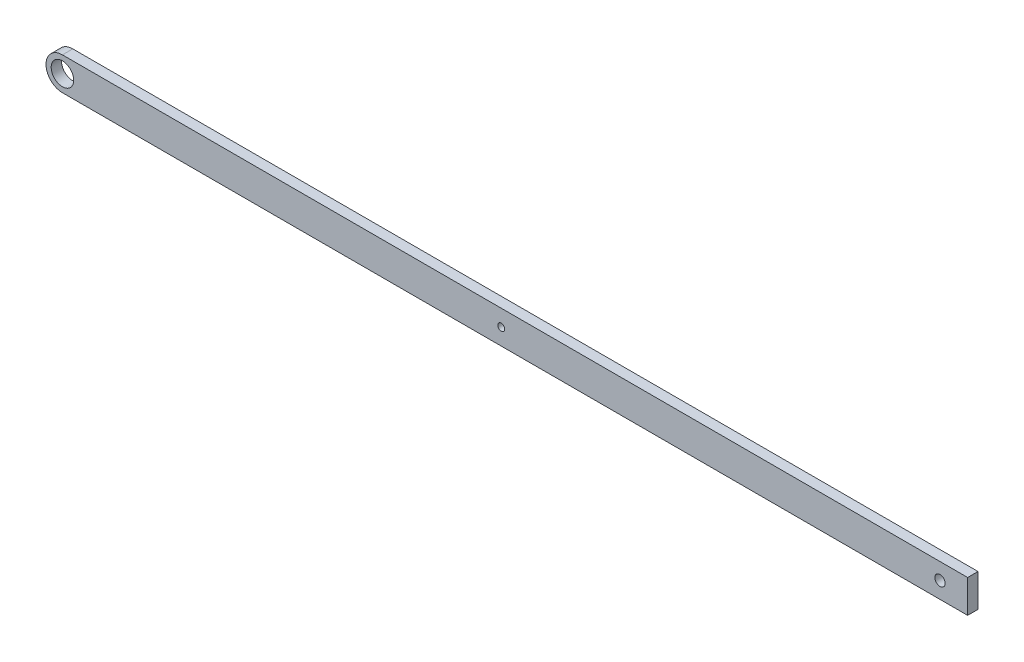
SolidWorks part; units mm, degrees
material "Gray Cast Iron"
ref_plane "Front Plane" through (0, 0, 0) normal (0, 0, 1) x (1, 0, 0)
ref_plane "Top Plane" through (0, 0, 0) normal (0, 1, 0) x (1, 0, 0)
ref_plane "Right Plane" through (0, 0, 0) normal (1, 0, 0) x (0, 0, -1)
sketch "Sketch1" plane through (0, 0, 0) normal (0, 0, 1) x (1, 0, 0)
  line L0 (0, -4.75) -> (262, -4.75)
  line L1 (262, -4.75) -> (262, 4.75)
  line L2 (262, 4.75) -> (0, 4.75)
  arc A0 (0, 4.75) -> (0, -4.75) centre (0, 0) ccw
extrude "Boss-Extrude1" add sketch "Sketch1" along normal mid plane 3
sketch "Sketch2" plane through (0, 0, 0) normal (0, 0, 1) x (1, 0, 0)
  circle A0 centre (0, 0) radius 3.25
  circle A1 centre (127, 0) radius 1
  circle A2 centre (254, 0) radius 1.5
  dimension "D1" = 6.5
  dimension "D2" = 2
  dimension "D3" = 3
extrude "Cut-Extrude1" cut sketch "Sketch2" against normal mid plane 40
